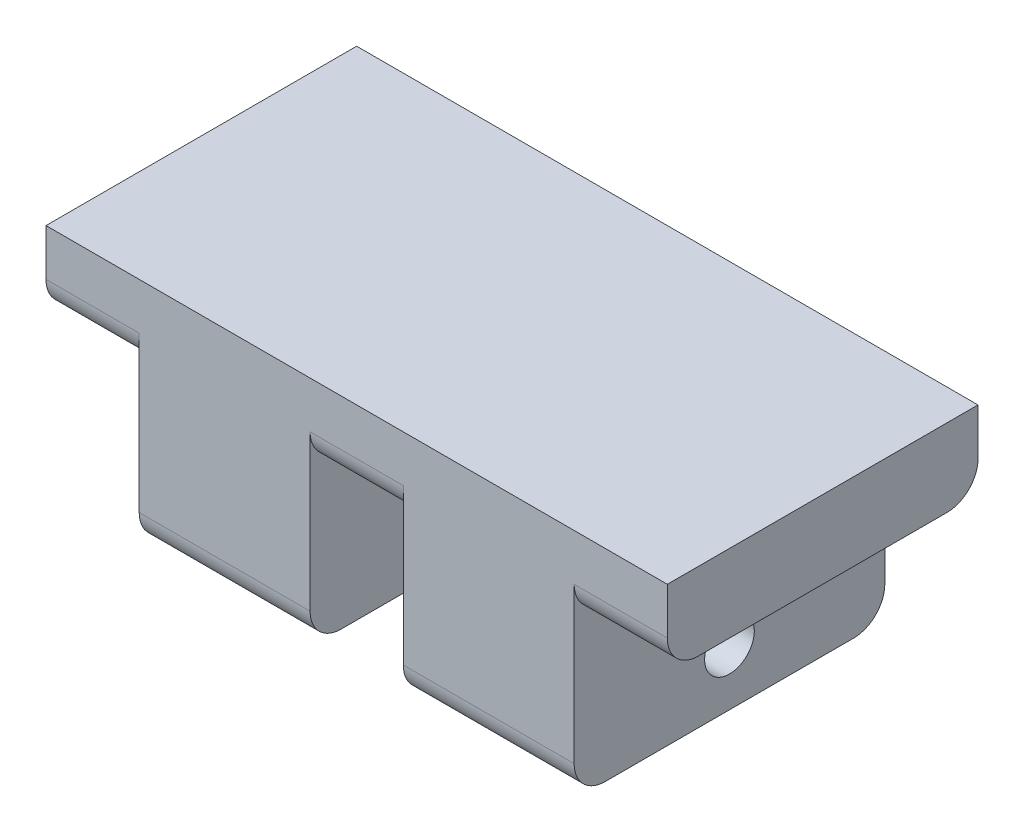
SolidWorks part; units mm, degrees
ref_plane "Front" through (0, 0, 0) normal (0, 0, 1) x (1, 0, 0)
ref_plane "Top" through (0, 0, 0) normal (0, 1, 0) x (1, 0, 0)
ref_plane "Right" through (0, 0, 0) normal (1, 0, 0) x (0, 0, -1)
sketch "Sketch1" plane through (0, 0, 0) normal (0, 0, 1) x (1, 0, 0)
  line L0 (0, 0) -> (0, 12.7)
  line L1 (0, 12.7) -> (-7.62, 12.7)
  line L2 (-7.62, 12.7) -> (-7.62, 19.05)
  line L3 (-7.62, 19.05) -> (43.18, 19.05)
  line L4 (43.18, 19.05) -> (43.18, 12.7)
  line L5 (43.18, 12.7) -> (35.56, 12.7)
  line L6 (35.56, 12.7) -> (35.56, 0)
  line L7 (35.56, 0) -> (21.59, 0)
  line L8 (21.59, 0) -> (21.59, 12.7)
  line L9 (21.59, 12.7) -> (13.97, 12.7)
  line L10 (13.97, 12.7) -> (13.97, 0)
  line L11 (13.97, 0) -> (0, 0)
  dimension "D1" = 50.8
  dimension "D2" = 12.7
  dimension "D3" = 12.7
  dimension "D4" = 12.7
  dimension "D5" = 7.62
  dimension "D6" = 7.62
  dimension "D7" = 13.97
  dimension "D8" = 13.97
  dimension "D9" = 6.35
extrude "Boss-Extrude1" add sketch "Sketch1" along normal blind 25.4
fillet "Fillet1" radius 2.54 4 edges at (6.985, 0, 0) (28.575, 0, 0) (28.575, 0, 25.4) (6.985, 0, 25.4)
sketch "Sketch2" plane through (35.56, 0, 0) normal (1, 0, 0) x (0, 0, -1)
  line L0 (-22.86, 0) -> (-2.54, 0) construction
  line L1 (0, 2.54) -> (0, 12.7) construction
  circle A0 centre (-12.7, 4.572) radius 2.032
  dimension "D1" = 4.572
  dimension "D2" = 4.064
  dimension "D3" = 12.7
extrude "Cut-Extrude1" cut sketch "Sketch2" against normal through all
fillet "Fillet2" radius 2.54 6 edges at (-3.81, 12.7, 0) (17.78, 12.7, 0) (39.37, 12.7, 0) (39.37, 12.7, 25.4) (17.78, 12.7, 25.4) (-3.81, 12.7, 25.4)
